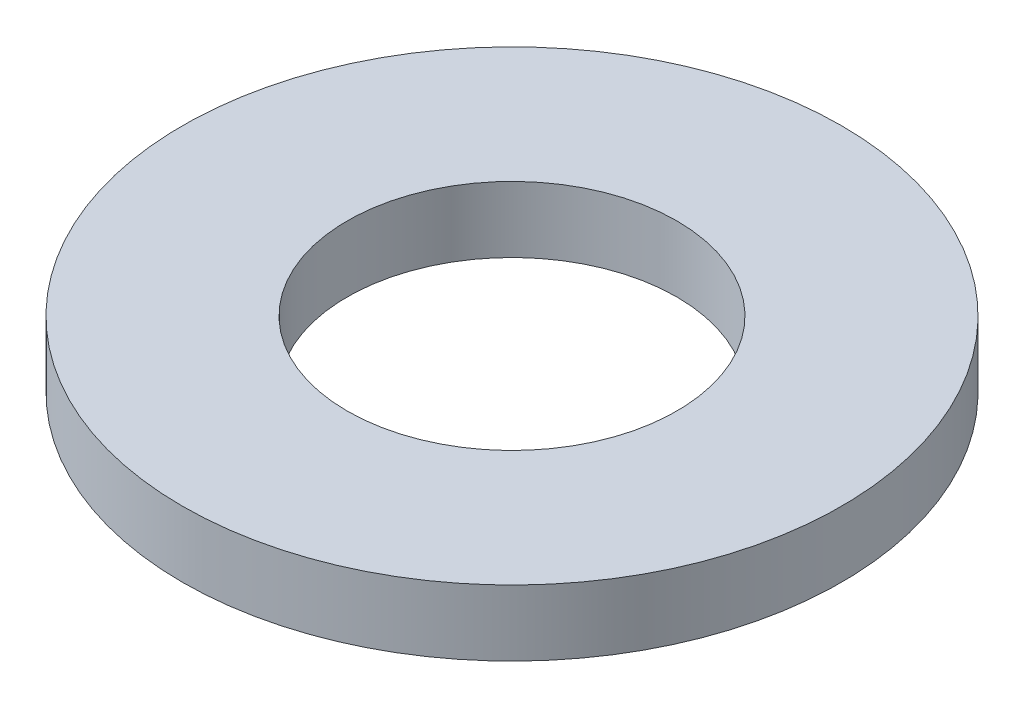
SolidWorks part; units mm, degrees
ref_plane "前视基准面" through (0, 0, 0) normal (0, 0, 1) x (1, 0, 0)
ref_plane "上视基准面" through (0, 0, 0) normal (0, 1, 0) x (1, 0, 0)
ref_plane "右视基准面" through (0, 0, 0) normal (1, 0, 0) x (0, 0, -1)
sketch "草图1" plane through (0, 0, 0) normal (0, 1, 0) x (1, 0, 0)
  circle A0 centre (0, 0) radius 250
  circle A1 centre (0, 0) radius 125
  dimension "D1" = 500
  dimension "D2" = 250
extrude "凸台-拉伸1" add sketch "草图1" along normal blind 50
